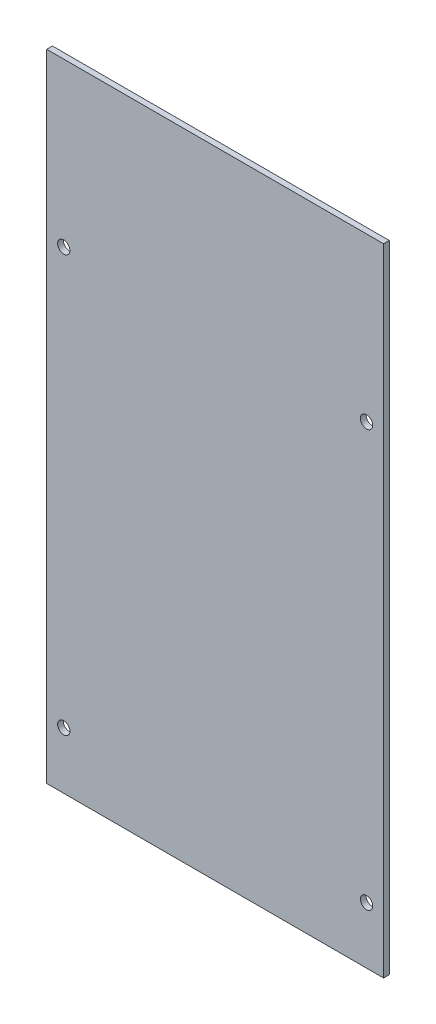
SolidWorks part; units mm, degrees
ref_plane "Front Plane" through (0, 0, 0) normal (0, 0, 1) x (1, 0, 0)
ref_plane "Top Plane" through (0, 0, 0) normal (0, 1, 0) x (1, 0, 0)
ref_plane "Right Plane" through (0, 0, 0) normal (1, 0, 0) x (0, 0, -1)
sketch "Sketch1" plane through (0, 0, 0) normal (0, 0, 1) x (1, 0, 0)
  line L1 (-89, 0) -> (89, 0)
  line L2 (-89, 0) -> (-89, 336)
  line L3 (-89, 336) -> (89, 336)
  line L4 (89, 0) -> (89, 336)
  line L5 (-89, 0) -> (89, 336) construction
  line L6 (-89, 336) -> (89, 0) construction
  point P4 (0, 168)
  point P5 (0, 0)
  point P6 (0, 0)
  dimension "D1" = 178
  dimension "D2" = 336
extrude "Boss-Extrude1" add sketch "Sketch1" along normal blind 3
sketch "Sketch2" plane through (0, 0, 3) normal (0, 0, 1) x (1, 0, 0)
  line L0 (89, 0) -> (89, 336) construction
  line L1 (-80, 250) -> (80, 250) construction
  line L2 (-80, 250) -> (-80, 30) construction
  line L3 (-80, 30) -> (80, 30) construction
  line L4 (80, 250) -> (80, 30) construction
  line L5 (-80, 250) -> (80, 30) construction
  line L6 (-80, 30) -> (80, 250) construction
  line L7 (-89, 0) -> (89, 0) construction
  circle A0 centre (-80, 250) radius 3.25
  circle A1 centre (80, 250) radius 3.25
  circle A2 centre (80, 30) radius 3.25
  circle A3 centre (-80, 30) radius 3.25
  point P4 (0, 140)
  dimension "D5" = 6.5
  dimension "D1" = 220
  dimension "D2" = 160
  dimension "D3" = 9
  dimension "D4" = 30
extrude "Cut-Extrude1" cut sketch "Sketch2" against normal through all both
